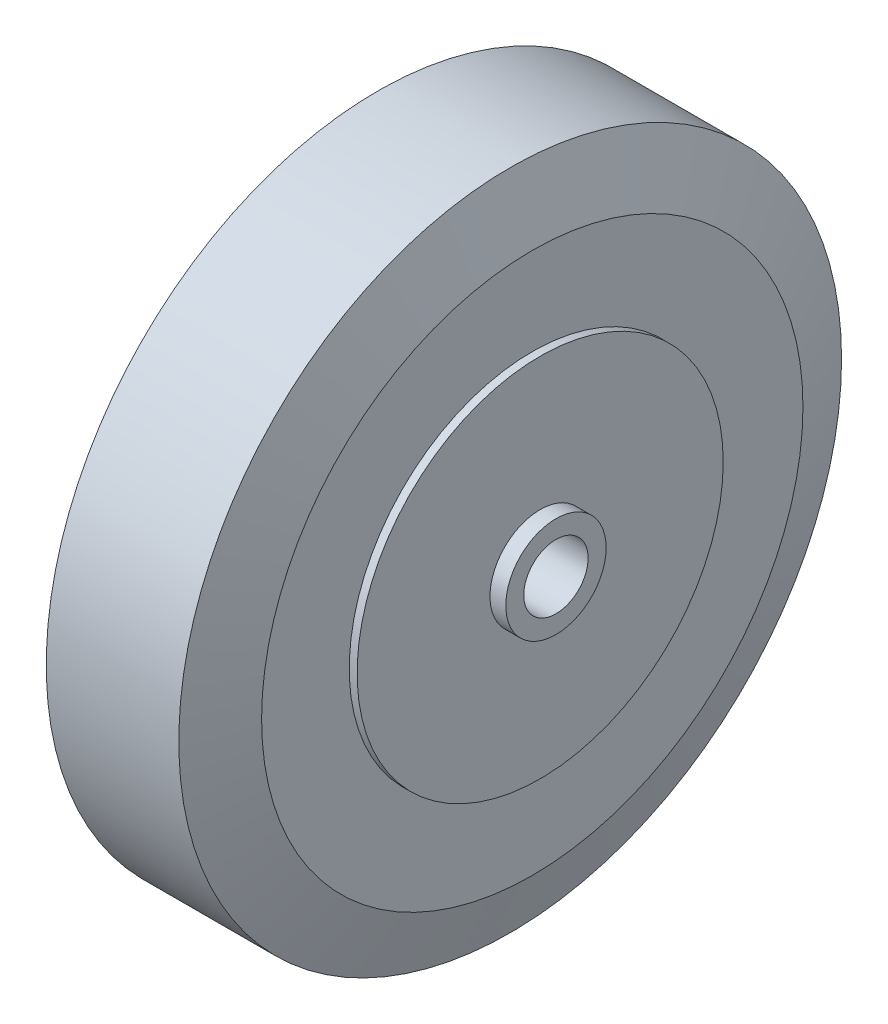
SolidWorks part; units mm, degrees
ref_plane "Płaszczyzna przednia" through (0, 0, 0) normal (0, 0, 1) x (1, 0, 0)
ref_plane "Płaszczyzna górna" through (0, 0, 0) normal (0, 1, 0) x (1, 0, 0)
ref_plane "Płaszczyzna prawa" through (0, 0, 0) normal (1, 0, 0) x (0, 0, -1)
sketch "Szkic2" plane through (0, 0, 0) normal (0, 0, 1) x (1, 0, 0)
  line L0 (0, 10.2) -> (-35.5, 10.2)
  line L1 (-35.5, 10.2) -> (-35.5, 15.9)
  line L2 (-35.5, 15.9) -> (-30.5, 15.9)
  line L3 (-30.5, 15.9) -> (-30.5, 58)
  line L4 (-30.5, 58) -> (-28, 58)
  line L5 (-28, 58) -> (-28, 85.7677)
  line L6 (-28, 85.7677) -> (-21, 105)
  line L7 (-21, 105) -> (0, 105)
  line L8 (0, 105) -> (0, 10.2)
  line L9 (0, 0) -> (-76.3858, 0) construction
  line L10 (0, 0) -> (0, -71) construction
  point P12 (-35.5, 13.05)
  point P14 (-30.5, 36.95)
  point P15 (-28, 86.3513)
  dimension "D1" = 210
  dimension "D2" = 20.4
  dimension "D3" = 31.8
  dimension "D4" = 116
  dimension "D5" = 71
  dimension "D6" = 61
  dimension "D7" = 56
  dimension "D8" = 42
  dimension "D9" = 160
revolve "Obrót1" add sketch "Szkic2" angle 360 about L9
mirror "Lustro2" of "Obrót1"
